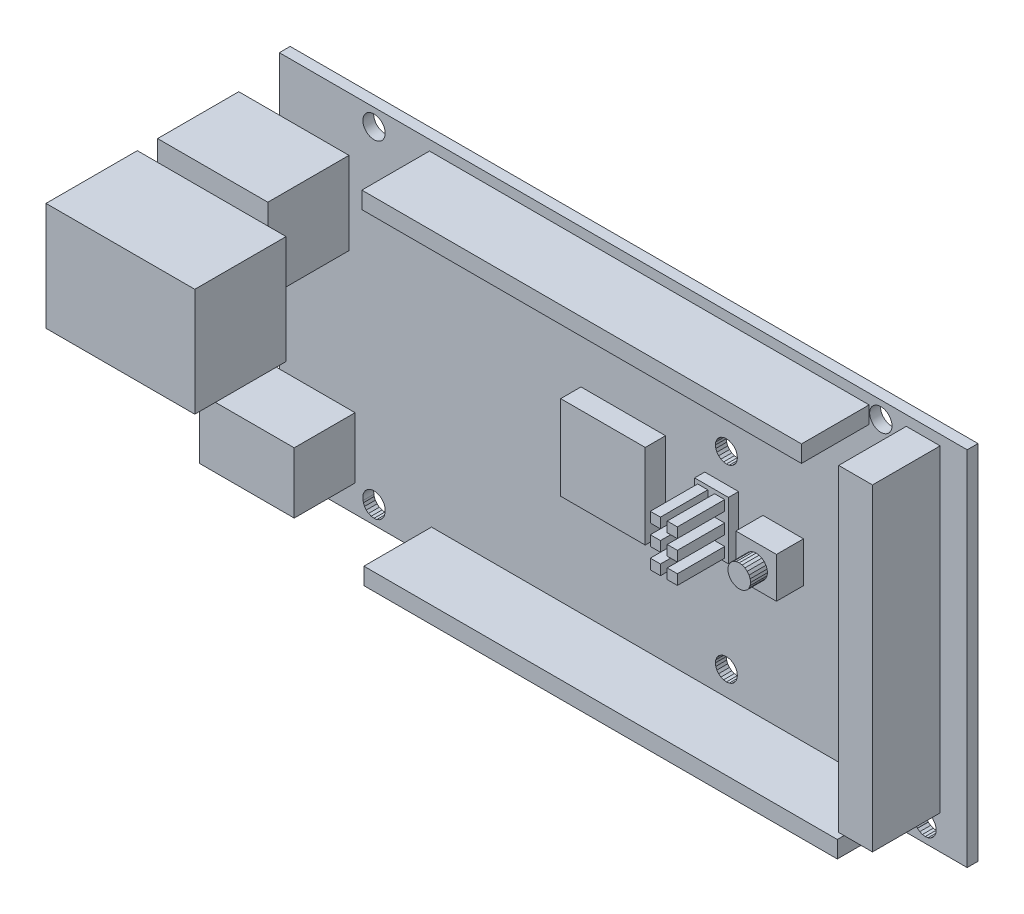
SolidWorks part; units mm, degrees
ref_plane "Спереди" through (0, 0, 0) normal (0, 0, 1) x (1, 0, 0)
ref_plane "Сверху" through (0, 0, 0) normal (0, 1, 0) x (1, 0, 0)
ref_plane "Справа" through (0, 0, 0) normal (1, 0, 0) x (0, 0, -1)
ref_plane "Плоскость4" through (0, 0, 0) normal (0, 0, -1) x (-1, 0, 0)
sketch "Эскиз1" plane through (0, 0, 0) normal (0, 0, -1) x (-1, 0, 0)
  line L0 (50.85, 26.75) -> (-50.85, 26.75)
  line L1 (-50.85, 26.75) -> (-50.85, -26.75)
  line L2 (-50.85, -26.75) -> (50.85, -26.75)
  line L3 (50.85, -26.75) -> (50.85, 26.75)
extrude "Бобышка-Вытянуть1" add sketch "Эскиз1" against normal blind 1.6
sketch "Эскиз2" plane through (0, 0, 1.6) normal (0, 0, 1) x (1, 0, 0)
  line L0 (-56.85, 18.75) -> (-40.55, 18.75)
  line L1 (-40.55, 18.75) -> (-40.55, 6.55)
  line L2 (-40.55, 6.55) -> (-56.85, 6.55)
  line L3 (-56.85, 6.55) -> (-56.85, 18.75)
extrude "Бобышка-Вытянуть2" add sketch "Эскиз2" along normal blind 12
sketch "Эскиз3" plane through (0, 0, 1.6) normal (0, 0, 1) x (1, 0, 0)
  line L0 (-39.65, -22.75) -> (-53.65, -22.75)
  line L1 (-53.65, -22.75) -> (-53.65, -13.75)
  line L2 (-53.65, -13.75) -> (-39.65, -13.75)
  line L3 (-39.65, -13.75) -> (-39.65, -22.75)
extrude "Бобышка-Вытянуть3" add sketch "Эскиз3" along normal blind 9
sketch "Эскиз5" plane through (0, 0, 0) normal (0, 0, -1) x (-1, 0, 0)
  line L0 (-16.6573, -19.9625) -> (-16.3991, -20.299)
  line L1 (-16.3991, -20.299) -> (-16.0625, -20.5573)
  line L2 (-16.0625, -20.5573) -> (-15.6706, -20.7196)
  line L3 (-15.6706, -20.7196) -> (-15.25, -20.775)
  line L4 (-15.25, -20.775) -> (-14.8294, -20.7196)
  line L5 (-14.8294, -20.7196) -> (-14.4375, -20.5573)
  line L6 (-14.4375, -20.5573) -> (-14.101, -20.299)
  line L7 (-14.101, -20.299) -> (-13.8427, -19.9625)
  line L8 (-13.8427, -19.9625) -> (-13.6804, -19.5706)
  line L9 (-13.6804, -19.5706) -> (-13.625, -19.15)
  line L10 (-13.625, -19.15) -> (-13.6804, -18.7294)
  line L11 (-13.6804, -18.7294) -> (-13.8427, -18.3375)
  line L12 (-13.8427, -18.3375) -> (-14.101, -18.0009)
  line L13 (-14.101, -18.0009) -> (-14.4375, -17.7427)
  line L14 (-14.4375, -17.7427) -> (-14.8294, -17.5804)
  line L15 (-14.8294, -17.5804) -> (-15.25, -17.525)
  line L16 (-15.25, -17.525) -> (-15.6706, -17.5804)
  line L17 (-15.6706, -17.5804) -> (-16.0625, -17.7427)
  line L18 (-16.0625, -17.7427) -> (-16.3991, -18.0009)
  line L19 (-16.3991, -18.0009) -> (-16.6573, -18.3375)
  line L20 (-16.6573, -18.3375) -> (-16.8196, -18.7294)
  line L21 (-16.8196, -18.7294) -> (-16.875, -19.15)
  line L22 (-16.875, -19.15) -> (-16.8196, -19.5706)
  line L23 (-16.8196, -19.5706) -> (-16.6573, -19.9625)
extrude "Вырез-Вытянуть2" cut sketch "Эскиз5" against normal through all
sketch "Эскиз7" plane through (0, 0, 0) normal (0, 0, -1) x (-1, 0, 0)
  line L0 (-43.5009, -23.1009) -> (-43.8375, -22.8427)
  line L1 (-43.8375, -22.8427) -> (-44.2294, -22.6804)
  line L2 (-44.2294, -22.6804) -> (-44.65, -22.625)
  line L3 (-44.65, -22.625) -> (-45.0706, -22.6804)
  line L4 (-45.0706, -22.6804) -> (-45.4625, -22.8427)
  line L5 (-45.4625, -22.8427) -> (-45.7991, -23.1009)
  line L6 (-45.7991, -23.1009) -> (-46.0573, -23.4375)
  line L7 (-46.0573, -23.4375) -> (-46.2196, -23.8294)
  line L8 (-46.2196, -23.8294) -> (-46.275, -24.25)
  line L9 (-46.275, -24.25) -> (-46.2196, -24.6706)
  line L10 (-46.2196, -24.6706) -> (-46.0573, -25.0625)
  line L11 (-46.0573, -25.0625) -> (-45.7991, -25.399)
  line L12 (-45.7991, -25.399) -> (-45.4625, -25.6573)
  line L13 (-45.4625, -25.6573) -> (-45.0706, -25.8196)
  line L14 (-45.0706, -25.8196) -> (-44.65, -25.875)
  line L15 (-44.65, -25.875) -> (-44.2294, -25.8196)
  line L16 (-44.2294, -25.8196) -> (-43.8375, -25.6573)
  line L17 (-43.8375, -25.6573) -> (-43.5009, -25.399)
  line L18 (-43.5009, -25.399) -> (-43.2427, -25.0625)
  line L19 (-43.2427, -25.0625) -> (-43.0804, -24.6706)
  line L20 (-43.0804, -24.6706) -> (-43.025, -24.25)
  line L21 (-43.025, -24.25) -> (-43.0804, -23.8294)
  line L22 (-43.0804, -23.8294) -> (-43.2427, -23.4375)
  line L23 (-43.2427, -23.4375) -> (-43.5009, -23.1009)
extrude "Вырез-Вытянуть4" cut sketch "Эскиз7" against normal through all
sketch "Эскиз8" plane through (0, 0, 0) normal (0, 0, -1) x (-1, 0, 0)
  line L0 (-16.3991, 9.899) -> (-16.6573, 9.5625)
  line L1 (-16.6573, 9.5625) -> (-16.8196, 9.1706)
  line L2 (-16.8196, 9.1706) -> (-16.875, 8.75)
  line L3 (-16.875, 8.75) -> (-16.8196, 8.3294)
  line L4 (-16.8196, 8.3294) -> (-16.6573, 7.9375)
  line L5 (-16.6573, 7.9375) -> (-16.3991, 7.601)
  line L6 (-16.3991, 7.601) -> (-16.0625, 7.3427)
  line L7 (-16.0625, 7.3427) -> (-15.6706, 7.1804)
  line L8 (-15.6706, 7.1804) -> (-15.25, 7.125)
  line L9 (-15.25, 7.125) -> (-14.8294, 7.1804)
  line L10 (-14.8294, 7.1804) -> (-14.4375, 7.3427)
  line L11 (-14.4375, 7.3427) -> (-14.101, 7.601)
  line L12 (-14.101, 7.601) -> (-13.8427, 7.9375)
  line L13 (-13.8427, 7.9375) -> (-13.6804, 8.3294)
  line L14 (-13.6804, 8.3294) -> (-13.625, 8.75)
  line L15 (-13.625, 8.75) -> (-13.6804, 9.1706)
  line L16 (-13.6804, 9.1706) -> (-13.8427, 9.5625)
  line L17 (-13.8427, 9.5625) -> (-14.101, 9.899)
  line L18 (-14.101, 9.899) -> (-14.4375, 10.1573)
  line L19 (-14.4375, 10.1573) -> (-14.8294, 10.3196)
  line L20 (-14.8294, 10.3196) -> (-15.25, 10.375)
  line L21 (-15.25, 10.375) -> (-15.6706, 10.3196)
  line L22 (-15.6706, 10.3196) -> (-16.0625, 10.1573)
  line L23 (-16.0625, 10.1573) -> (-16.3991, 9.899)
extrude "Вырез-Вытянуть5" cut sketch "Эскиз8" against normal through all
sketch "Эскиз9" plane through (0, 0, 1.6) normal (0, 0, 1) x (1, 0, 0)
  line L0 (-35.2804, -24.6706) -> (-35.225, -24.25)
  line L1 (-35.225, -24.25) -> (-35.2804, -23.8294)
  line L2 (-35.2804, -23.8294) -> (-35.4427, -23.4375)
  line L3 (-35.4427, -23.4375) -> (-35.701, -23.1009)
  line L4 (-35.701, -23.1009) -> (-36.0375, -22.8427)
  line L5 (-36.0375, -22.8427) -> (-36.4294, -22.6804)
  line L6 (-36.4294, -22.6804) -> (-36.85, -22.625)
  line L7 (-36.85, -22.625) -> (-37.2706, -22.6804)
  line L8 (-37.2706, -22.6804) -> (-37.6625, -22.8427)
  line L9 (-37.6625, -22.8427) -> (-37.999, -23.1009)
  line L10 (-37.999, -23.1009) -> (-38.2573, -23.4375)
  line L11 (-38.2573, -23.4375) -> (-38.4196, -23.8294)
  line L12 (-38.4196, -23.8294) -> (-38.475, -24.25)
  line L13 (-38.475, -24.25) -> (-38.4196, -24.6706)
  line L14 (-38.4196, -24.6706) -> (-38.2573, -25.0625)
  line L15 (-38.2573, -25.0625) -> (-37.999, -25.399)
  line L16 (-37.999, -25.399) -> (-37.6625, -25.6573)
  line L17 (-37.6625, -25.6573) -> (-37.2706, -25.8196)
  line L18 (-37.2706, -25.8196) -> (-36.85, -25.875)
  line L19 (-36.85, -25.875) -> (-36.4294, -25.8196)
  line L20 (-36.4294, -25.8196) -> (-36.0375, -25.6573)
  line L21 (-36.0375, -25.6573) -> (-35.701, -25.399)
  line L22 (-35.701, -25.399) -> (-35.4427, -25.0625)
  line L23 (-35.4427, -25.0625) -> (-35.2804, -24.6706)
extrude "Вырез-Вытянуть6" cut sketch "Эскиз9" against normal through all
sketch "Эскиз10" plane through (0, 0, 1.6) normal (0, 0, 1) x (1, 0, 0)
  line L0 (20.65, 3.25) -> (26.65, 3.25)
  line L1 (26.65, 3.25) -> (26.65, -2.75)
  line L2 (26.65, -2.75) -> (20.65, -2.75)
  line L3 (20.65, -2.75) -> (20.65, 3.25)
extrude "Бобышка-Вытянуть4" add sketch "Эскиз10" along normal blind 4
sketch "Эскиз11" plane through (0, 0, 5.6) normal (0, 0, 1) x (1, 0, 0)
  line L0 (25.2679, 0.6835) -> (25.325, 0.25)
  line L1 (25.325, 0.25) -> (25.2679, -0.1835)
  line L2 (25.2679, -0.1835) -> (25.1006, -0.5875)
  line L3 (25.1006, -0.5875) -> (24.8344, -0.9344)
  line L4 (24.8344, -0.9344) -> (24.4875, -1.2006)
  line L5 (24.4875, -1.2006) -> (24.0835, -1.3679)
  line L6 (24.0835, -1.3679) -> (23.65, -1.425)
  line L7 (23.65, -1.425) -> (23.2165, -1.3679)
  line L8 (23.2165, -1.3679) -> (22.8125, -1.2006)
  line L9 (22.8125, -1.2006) -> (22.4656, -0.9344)
  line L10 (22.4656, -0.9344) -> (22.1994, -0.5875)
  line L11 (22.1994, -0.5875) -> (22.0321, -0.1835)
  line L12 (22.0321, -0.1835) -> (21.975, 0.25)
  line L13 (21.975, 0.25) -> (22.0321, 0.6835)
  line L14 (22.0321, 0.6835) -> (22.1994, 1.0875)
  line L15 (22.1994, 1.0875) -> (22.4656, 1.4344)
  line L16 (22.4656, 1.4344) -> (22.8125, 1.7006)
  line L17 (22.8125, 1.7006) -> (23.2165, 1.8679)
  line L18 (23.2165, 1.8679) -> (23.65, 1.925)
  line L19 (23.65, 1.925) -> (24.0835, 1.8679)
  line L20 (24.0835, 1.8679) -> (24.4875, 1.7006)
  line L21 (24.4875, 1.7006) -> (24.8344, 1.4344)
  line L22 (24.8344, 1.4344) -> (25.1006, 1.0875)
  line L23 (25.1006, 1.0875) -> (25.2679, 0.6835)
extrude "Бобышка-Вытянуть5" add sketch "Эскиз11" along normal blind 2.5
sketch "Эскиз12" plane through (-53.65, 0, 0) normal (-1, 0, 0) x (0, 0, 1)
  line L0 (7.9514, -21.2203) -> (8.5114, -20.7868)
  line L1 (8.5114, -20.7868) -> (8.9727, -20.2494)
  line L2 (8.9727, -20.2494) -> (9.3164, -19.6302)
  line L3 (9.3164, -19.6302) -> (9.5284, -18.9545)
  line L4 (9.5284, -18.9545) -> (9.6, -18.25)
  line L5 (9.6, -18.25) -> (9.5284, -17.5455)
  line L6 (9.5284, -17.5455) -> (9.3164, -16.8697)
  line L7 (9.3164, -16.8697) -> (8.9727, -16.2506)
  line L8 (8.9727, -16.2506) -> (8.5114, -15.7132)
  line L9 (8.5114, -15.7132) -> (7.9514, -15.2798)
  line L10 (7.9514, -15.2798) -> (7.3156, -14.9679)
  line L11 (7.3156, -14.9679) -> (6.63, -14.7904)
  line L12 (6.63, -14.7904) -> (5.9227, -14.7545)
  line L13 (5.9227, -14.7545) -> (5.2227, -14.8617)
  line L14 (5.2227, -14.8617) -> (4.5586, -15.1077)
  line L15 (4.5586, -15.1077) -> (3.9576, -15.4823)
  line L16 (3.9576, -15.4823) -> (3.4443, -15.9702)
  line L17 (3.4443, -15.9702) -> (3.0398, -16.5514)
  line L18 (3.0398, -16.5514) -> (2.7605, -17.2022)
  line L19 (2.7605, -17.2022) -> (2.618, -17.8959)
  line L20 (2.618, -17.8959) -> (2.618, -18.6041)
  line L21 (2.618, -18.6041) -> (2.7605, -19.2978)
  line L22 (2.7605, -19.2978) -> (3.0398, -19.9486)
  line L23 (3.0398, -19.9486) -> (3.4443, -20.5298)
  line L24 (3.4443, -20.5298) -> (3.9576, -21.0177)
  line L25 (3.9576, -21.0177) -> (4.5586, -21.3923)
  line L26 (4.5586, -21.3923) -> (5.2227, -21.6383)
  line L27 (5.2227, -21.6383) -> (5.9227, -21.7455)
  line L28 (5.9227, -21.7455) -> (6.63, -21.7096)
  line L29 (6.63, -21.7096) -> (7.3156, -21.5321)
  line L30 (7.3156, -21.5321) -> (7.9514, -21.2203)
extrude "Вырез-Вытянуть7" cut sketch "Эскиз12" against normal blind 11
sketch "Эскиз13" plane through (-42.65, 0, 0) normal (-1, 0, 0) x (0, 0, 1)
  line L0 (7.6, -18.25) -> (7.5489, -18.6382)
  line L1 (7.5489, -18.6382) -> (7.399, -19)
  line L2 (7.399, -19) -> (7.1607, -19.3107)
  line L3 (7.1607, -19.3107) -> (6.85, -19.549)
  line L4 (6.85, -19.549) -> (6.4882, -19.6989)
  line L5 (6.4882, -19.6989) -> (6.1, -19.75)
  line L6 (6.1, -19.75) -> (5.7118, -19.6989)
  line L7 (5.7118, -19.6989) -> (5.35, -19.549)
  line L8 (5.35, -19.549) -> (5.0393, -19.3107)
  line L9 (5.0393, -19.3107) -> (4.801, -19)
  line L10 (4.801, -19) -> (4.6511, -18.6382)
  line L11 (4.6511, -18.6382) -> (4.6, -18.25)
  line L12 (4.6, -18.25) -> (4.6511, -17.8618)
  line L13 (4.6511, -17.8618) -> (4.801, -17.5)
  line L14 (4.801, -17.5) -> (5.0393, -17.1893)
  line L15 (5.0393, -17.1893) -> (5.35, -16.951)
  line L16 (5.35, -16.951) -> (5.7118, -16.8011)
  line L17 (5.7118, -16.8011) -> (6.1, -16.75)
  line L18 (6.1, -16.75) -> (6.4882, -16.8011)
  line L19 (6.4882, -16.8011) -> (6.85, -16.951)
  line L20 (6.85, -16.951) -> (7.1607, -17.1893)
  line L21 (7.1607, -17.1893) -> (7.399, -17.5)
  line L22 (7.399, -17.5) -> (7.5489, -17.8618)
  line L23 (7.5489, -17.8618) -> (7.6, -18.25)
extrude "Бобышка-Вытянуть6" add sketch "Эскиз13" along normal blind 11
sketch "Эскиз14" plane through (0, 0, 1.6) normal (0, 0, 1) x (1, 0, 0)
  line L0 (12.05, -4) -> (12.05, 4.5)
  line L1 (12.05, 4.5) -> (17.05, 4.5)
  line L2 (17.05, 4.5) -> (17.05, -4)
  line L3 (17.05, -4) -> (12.05, -4)
extrude "Бобышка-Вытянуть7" add sketch "Эскиз14" along normal blind 1.5
sketch "Эскиз15" plane through (0, 0, 3.1) normal (0, 0, 1) x (1, 0, 0)
  line L0 (16.5, -0.55) -> (15, -0.55)
  line L1 (15, -0.55) -> (15, 0.95)
  line L2 (15, 0.95) -> (16.5, 0.95)
  line L3 (16.5, 0.95) -> (16.5, -0.55)
extrude "Бобышка-Вытянуть8" add sketch "Эскиз15" along normal blind 7
sketch "Эскиз16" plane through (0, 0, 3.1) normal (0, 0, 1) x (1, 0, 0)
  line L0 (15, 2.45) -> (15, 3.95)
  line L1 (15, 3.95) -> (16.5, 3.95)
  line L2 (16.5, 3.95) -> (16.5, 2.45)
  line L3 (16.5, 2.45) -> (15, 2.45)
extrude "Бобышка-Вытянуть9" add sketch "Эскиз16" along normal blind 7
sketch "Эскиз17" plane through (0, 0, 3.1) normal (0, 0, 1) x (1, 0, 0)
  line L0 (12.5, 2.45) -> (12.5, 3.95)
  line L1 (12.5, 3.95) -> (14, 3.95)
  line L2 (14, 3.95) -> (14, 2.45)
  line L3 (14, 2.45) -> (12.5, 2.45)
extrude "Бобышка-Вытянуть10" add sketch "Эскиз17" along normal blind 7
sketch "Эскиз18" plane through (0, 0, 3.1) normal (0, 0, 1) x (1, 0, 0)
  line L0 (12.5, -0.55) -> (12.5, 0.95)
  line L1 (12.5, 0.95) -> (14, 0.95)
  line L2 (14, 0.95) -> (14, -0.55)
  line L3 (14, -0.55) -> (12.5, -0.55)
extrude "Бобышка-Вытянуть11" add sketch "Эскиз18" along normal blind 7
sketch "Эскиз19" plane through (0, 0, 1.6) normal (0, 0, 1) x (1, 0, 0)
  line L0 (36.35, 25.25) -> (36.35, 22.75)
  line L1 (36.35, 22.75) -> (-28.65, 22.75)
  line L2 (-28.65, 22.75) -> (-28.65, 25.25)
  line L3 (-28.65, 25.25) -> (36.35, 25.25)
extrude "Бобышка-Вытянуть12" add sketch "Эскиз19" along normal blind 10
sketch "Эскиз20" plane through (0, 0, 3.1) normal (0, 0, 1) x (1, 0, 0)
  line L0 (12.5, -3.55) -> (12.5, -2.05)
  line L1 (12.5, -2.05) -> (14, -2.05)
  line L2 (14, -2.05) -> (14, -3.55)
  line L3 (14, -3.55) -> (12.5, -3.55)
extrude "Бобышка-Вытянуть13" add sketch "Эскиз20" along normal blind 7
sketch "Эскиз21" plane through (0, 0, 3.1) normal (0, 0, 1) x (1, 0, 0)
  line L0 (15, -3.55) -> (15, -2.05)
  line L1 (15, -2.05) -> (16.5, -2.05)
  line L2 (16.5, -2.05) -> (16.5, -3.55)
  line L3 (16.5, -3.55) -> (15, -3.55)
extrude "Бобышка-Вытянуть14" add sketch "Эскиз21" along normal blind 7
sketch "Эскиз22" plane through (0, 0, 1.6) normal (0, 0, 1) x (1, 0, 0)
  line L0 (-28.35, -22.75) -> (41.65, -22.75)
  line L1 (41.65, -22.75) -> (41.65, -25.25)
  line L2 (41.65, -25.25) -> (-28.35, -25.25)
  line L3 (-28.35, -25.25) -> (-28.35, -22.75)
extrude "Бобышка-Вытянуть15" add sketch "Эскиз22" along normal blind 10
sketch "Эскиз23" plane through (-56.85, 0, 0) normal (-1, 0, 0) x (0, 0, 1)
  line L0 (12.6, 7.65) -> (12.6, 17.65)
  line L1 (12.6, 17.65) -> (2.6, 17.65)
  line L2 (2.6, 17.65) -> (2.6, 7.65)
  line L3 (2.6, 7.65) -> (12.6, 7.65)
extrude "Вырез-Вытянуть8" cut sketch "Эскиз23" against normal blind 12
sketch "Эскиз24" plane through (-44.85, 0, 0) normal (-1, 0, 0) x (0, 0, 1)
  line L0 (5.1, 15.15) -> (10.1, 15.15)
  line L1 (10.1, 15.15) -> (10.1, 10.15)
  line L2 (10.1, 10.15) -> (5.1, 10.15)
  line L3 (5.1, 10.15) -> (5.1, 15.15)
extrude "Бобышка-Вытянуть16" add sketch "Эскиз24" along normal blind 12
sketch "Эскиз25" plane through (0, 0, 1.6) normal (0, 0, 1) x (1, 0, 0)
  line L0 (-6.25, -6.25) -> (-6.25, 6.25)
  line L1 (-6.25, 6.25) -> (6.25, 6.25)
  line L2 (6.25, 6.25) -> (6.25, -6.25)
  line L3 (6.25, -6.25) -> (-6.25, -6.25)
extrude "Бобышка-Вытянуть17" add sketch "Эскиз25" along normal blind 3
sketch "Эскиз26" plane through (0, 0, 1.6) normal (0, 0, 1) x (1, 0, 0)
  line L0 (46.85, -21.75) -> (41.85, -21.75)
  line L1 (41.85, -21.75) -> (41.85, 25.25)
  line L2 (41.85, 25.25) -> (46.85, 25.25)
  line L3 (46.85, 25.25) -> (46.85, -21.75)
extrude "Бобышка-Вытянуть18" add sketch "Эскиз26" along normal blind 10
sketch "Эскиз27" plane through (0, 0, 0) normal (0, 0, -1) x (-1, 0, 0)
  circle A0 centre (-44.43, -24.01) radius 1.65
  circle A1 centre (36.85, 24.25) radius 1.65
  circle A2 centre (-38.08, 24.25) radius 1.65
  circle A3 centre (36.85, -24.01) radius 1.65
  dimension "D1" = 3.3
  dimension "D2" = 3.3
  dimension "D3" = 3.3
  dimension "D4" = 3.3
  dimension "D5" = 74.93
  dimension "D6" = 81.28
  dimension "D7" = 48.26
extrude "Вырез-Вытянуть9" cut sketch "Эскиз27" against normal through all
sketch "Sketch1" plane through (0, 0, 13.6) normal (0, 0, 1) x (1, 0, 0)
  line L0 (-56.85, 18.75) -> (-56.85, 6.55) construction
  line L1 (-54.35, 21.2) -> (-32.35, 21.2)
  line L2 (-54.35, 21.2) -> (-54.35, 5.2)
  line L3 (-54.35, 5.2) -> (-32.35, 5.2)
  line L4 (-32.35, 21.2) -> (-32.35, 5.2)
  line L5 (-40.55, 18.75) -> (-56.85, 18.75) construction
  dimension "D1" = 22
  dimension "D2" = 16
  dimension "D3" = 2.5
  dimension "D4" = 2.45
extrude "Boss-Extrude1" add sketch "Sketch1" along normal blind 13.5 from offset 5.5 separate body
sketch "Sketch2" plane through (-54.35, 0, 0) normal (-1, 0, 0) x (0, 0, 1)
  line L0 (32.6, 21.2) -> (32.6, 5.2) construction
  line L1 (29.9, 18.6) -> (23.7, 18.6)
  line L2 (29.9, 18.6) -> (29.9, 7.4)
  line L3 (29.9, 7.4) -> (23.7, 7.4)
  line L4 (23.7, 18.6) -> (23.7, 7.4)
  line L5 (32.6, 5.2) -> (19.1, 5.2) construction
  line L6 (32.6, 21.2) -> (19.1, 21.2) construction
  line L7 (19.1, 21.2) -> (19.1, 5.2) construction
  line L9 (23.7, 16.4) -> (20.7543, 16.4)
  line L10 (23.7, 16.4) -> (23.7, 10)
  line L11 (23.7, 10) -> (20.7543, 10)
  line L12 (20.7543, 16.4) -> (20.7543, 10)
  dimension "D1" = 2.7
  dimension "D2" = 2.2
  dimension "D3" = 2.6
  dimension "D4" = 4.6
  dimension "D5" = 4.8
  dimension "D6" = 4.8
extrude "Cut-Extrude1" cut sketch "Sketch2" against normal blind 13.5 contours L1 L4 L3 L2 | L9 L12 L11 L4
